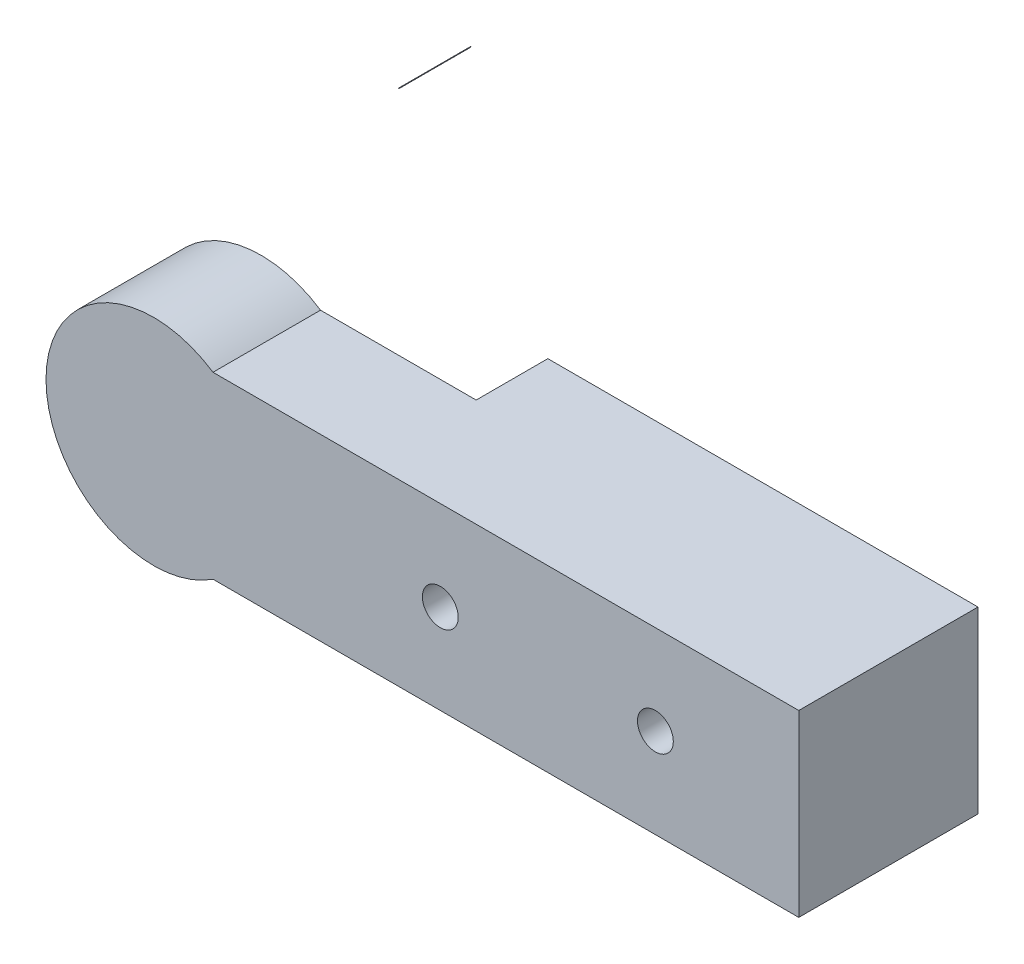
SolidWorks part; units mm, degrees
ref_plane "Front Plane" through (0, 0, 0) normal (0, 0, 1) x (1, 0, 0)
ref_plane "Top Plane" through (0, 0, 0) normal (0, 1, 0) x (1, 0, 0)
ref_plane "Right Plane" through (0, 0, 0) normal (1, 0, 0) x (0, 0, -1)
sketch "Sketch2" plane through (0, 0, 0) normal (0, 0, 1) x (1, 0, 0)
  line L1 (0, 12.5) -> (90, 12.5)
  line L2 (0, 12.5) -> (0, -12.5)
  line L3 (0, -12.5) -> (90, -12.5)
  line L4 (90, 12.5) -> (90, -12.5)
  circle A0 centre (0, 0) radius 15
  circle A1 centre (40, 0) radius 2.5
  circle A2 centre (70, 0) radius 2.5
  dimension "D1" = 40
  dimension "D2" = 30
  dimension "D7" = 5
  dimension "D8" = 5
  dimension "D3" = 90
  dimension "D4" = 25
  dimension "D5" = 12.5
  dimension "D6" = 30
extrude "Boss-Extrude1" add sketch "Sketch2" along normal blind 15 contours L1 A0 L3 L2 | L3 A0 L1 L2 | A0 L3 L4 L1 A2 A1
sketch "Sketch3" plane through (0, 0, 0) normal (0, 0, -1) x (-1, 0, 0)
  line L0 (-8.2916, -12.5) -> (-90, -12.5) construction
  line L1 (-90, 12.5) -> (-30, 12.5)
  line L2 (-90, 12.5) -> (-90, -12.5)
  line L3 (-90, -12.5) -> (-30, -12.5)
  line L4 (-30, 12.5) -> (-30, -12.5)
  circle A0 centre (-19.2259, 44.7714) radius 0.0357
  circle A2 centre (-40, 0) radius 2.5
  circle A3 centre (-70, 0) radius 2.5
  dimension "D1" = 60
extrude "Boss-Extrude2" add sketch "Sketch3" along normal blind 10
